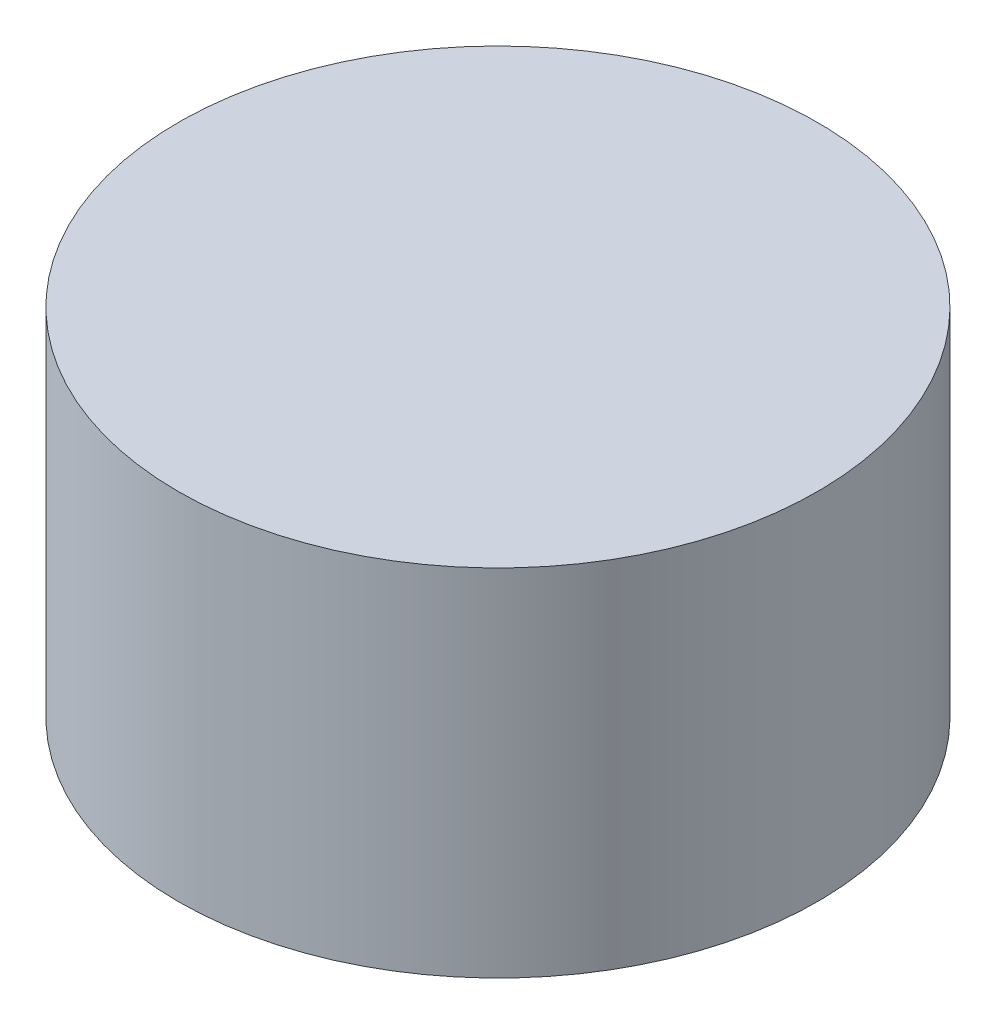
SolidWorks part; units mm, degrees
ref_plane "Front Plane" through (0, 0, 0) normal (0, 0, 1) x (1, 0, 0)
ref_plane "Top Plane" through (0, 0, 0) normal (0, 1, 0) x (1, 0, 0)
ref_plane "Right Plane" through (0, 0, 0) normal (1, 0, 0) x (0, 0, -1)
sketch "Sketch1" plane through (0, 0, 0) normal (0, 1, 0) x (1, 0, 0)
  circle A0 centre (0, 0) radius 9
  dimension "D1" = 18
extrude "Boss-Extrude1" add sketch "Sketch1" along normal blind 10
